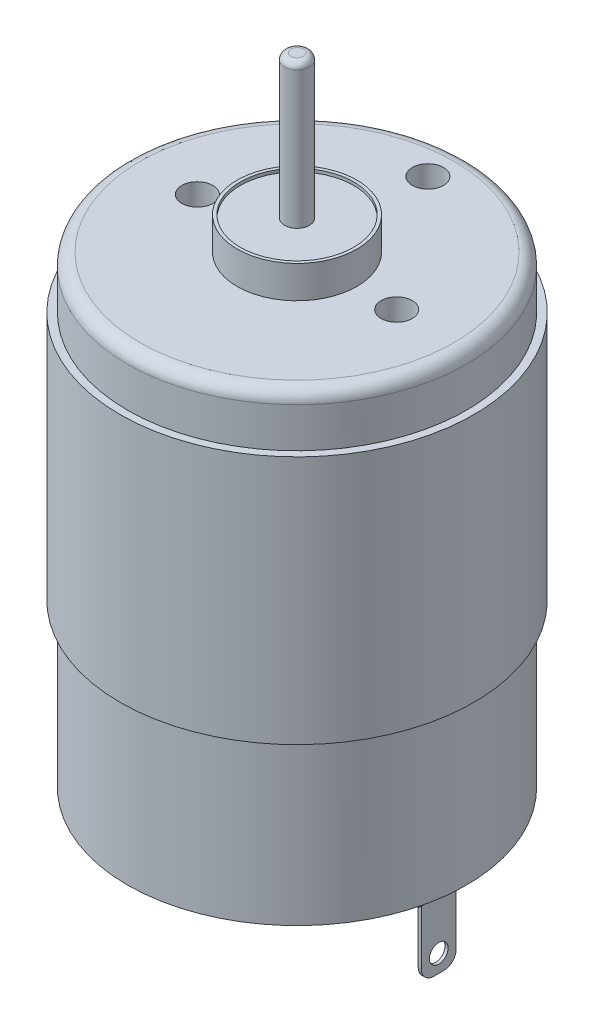
SolidWorks part; units mm, degrees
ref_plane "Plano frontal" through (0, 0, 0) normal (0, 0, 1) x (1, 0, 0)
ref_plane "Plano superior" through (0, 0, 0) normal (0, 1, 0) x (1, 0, 0)
ref_plane "Plano direito" through (0, 0, 0) normal (1, 0, 0) x (0, 0, -1)
sketch "Esboço1" plane through (0, 0, 0) normal (0, 1, 0) x (1, 0, 0)
  circle A0 centre (0, 0) radius 13.6
  dimension "D1" = 27.2
extrude "Ressalto-extrusão1" add sketch "Esboço1" along normal blind 37.2
sketch "Esboço2" plane through (0, 37.2, 0) normal (0, 1, 0) x (1, 0, 0)
  circle A0 centre (0, 0) radius 4.8
  dimension "D1" = 9.6
extrude "Ressalto-extrusão2" add sketch "Esboço2" along normal blind 2.6
sketch "Esboço3" plane through (0, 39.8, 0) normal (0, 1, 0) x (1, 0, 0)
  circle A0 centre (0, 0) radius 4.55
  circle A1 centre (0, 0) radius 4.8 construction
  dimension "D1" = 0.25
extrude "Corte-extrusão1" cut sketch "Esboço3" against normal blind 0.25
sketch "Esboço4" plane through (0, 39.55, 0) normal (0, 1, 0) x (1, 0, 0)
  circle A0 centre (0, 0) radius 1
  dimension "D1" = 2
extrude "Ressalto-extrusão3" add sketch "Esboço4" along normal blind 11.5
fillet "Filete1" radius 0.5 1 edges at (0, 51.05, 1)
sketch "Esboço5" plane through (0, 37.2, 0) normal (0, 1, 0) x (1, 0, 0)
  line L0 (0, 13.6) -> (0, -13.6) construction
  circle A0 centre (-8, 0) radius 1.25
  circle A1 centre (0, 0) radius 13.6 construction
  circle A2 centre (8, 0) radius 1.25
  dimension "D1" = 2.5
  dimension "D2" = 8
extrude "Corte-extrusão2" cut sketch "Esboço5" against normal blind 2
sketch "Esboço6" plane through (0, 37.2, 0) normal (0, 1, 0) x (1, 0, 0)
  circle A0 centre (0, 10.5) radius 1.25
  dimension "D1" = 2.5
  dimension "D2" = 10.5
extrude "Corte-extrusão3" cut sketch "Esboço6" against normal blind 2
sketch "Esboço7" plane through (0, 0, 0) normal (0, -1, 0) x (1, 0, 0)
  circle A0 centre (0, 0) radius 9.5
  circle A1 centre (0, 0) radius 13.35
  circle A2 centre (0, 0) radius 13.6 construction
  dimension "D1" = 19
  dimension "D2" = 0.25
extrude "Corte-extrusão4" cut sketch "Esboço7" against normal blind 0.25
fillet "Filete2" radius 0.2 1 edges at (0, 0, -9.5)
sketch "Esboço8" plane through (0, 0, 0) normal (0, -1, 0) x (1, 0, 0)
  circle A0 centre (0, 0) radius 4.8
  dimension "D1" = 9.6
extrude "Ressalto-extrusão4" add sketch "Esboço8" along normal blind 2.2
sketch "Esboço9" plane through (0, -2.2, 0) normal (0, -1, 0) x (1, 0, 0)
  circle A0 centre (0, 0) radius 4.55
  circle A1 centre (0, 0) radius 4.8 construction
  dimension "D1" = 0.25
extrude "Corte-extrusão5" cut sketch "Esboço9" against normal blind 0.25
sketch "Esboço10" plane through (0, -1.95, 0) normal (0, -1, 0) x (1, 0, 0)
  circle A0 centre (0, 0) radius 1
  dimension "D1" = 2
extrude "Ressalto-extrusão5" add sketch "Esboço10" along normal blind 2.3
fillet "Filete3" radius 0.5 1 edges at (0, -4.25, -1)
fillet "Filete4" radius 1 1 edges at (0, 37.2, 13.6)
sketch "Esboço11" plane through (0, 0.25, 0) normal (0, -1, 0) x (1, 0, 0)
  line L0 (0, 13.35) -> (0, -13.35) construction
  line L1 (-12, -2.25) -> (-10.5, -2.25)
  line L2 (-12, -2.25) -> (-12, 2.25)
  line L3 (-12, 2.25) -> (-10.5, 2.25)
  line L4 (-10.5, -2.25) -> (-10.5, 2.25)
  line L5 (-12, -2.25) -> (-10.5, 2.25) construction
  line L6 (-12, 2.25) -> (-10.5, -2.25) construction
  line L7 (12, 2.25) -> (10.5, -2.25) construction
  line L8 (12, -2.25) -> (10.5, 2.25) construction
  line L9 (10.5, -2.25) -> (10.5, 2.25)
  line L10 (12, 2.25) -> (10.5, 2.25)
  line L11 (12, -2.25) -> (12, 2.25)
  line L12 (12, -2.25) -> (10.5, -2.25)
  circle A0 centre (0, 0) radius 13.35 construction
  circle A1 centre (0, 0) radius 13.35 construction
  point P0 (-11.25, 0)
  point P18 (11.25, 0)
  dimension "D1" = 1.5
  dimension "D2" = 4.5
  dimension "D3" = 12
  dimension "D4" = 0
extrude "Ressalto-extrusão6" add sketch "Esboço11" along normal blind 1.5
sketch "Esboço12" plane through (0, -1.25, 0) normal (0, -1, 0) x (1, 0, 0)
  line L0 (-10.5, 2.25) -> (-12, 2.25) construction
  line L1 (-11.375, -1.4) -> (-11.125, -1.4)
  line L2 (-11.375, -1.4) -> (-11.375, 1.4)
  line L3 (-11.375, 1.4) -> (-11.125, 1.4)
  line L4 (-11.125, -1.4) -> (-11.125, 1.4)
  line L5 (-11.375, -1.4) -> (-11.125, 1.4) construction
  line L6 (-11.375, 1.4) -> (-11.125, -1.4) construction
  line L7 (0, 13.6) -> (0, -13.6) construction
  line L8 (11.375, 1.4) -> (11.125, -1.4) construction
  line L9 (11.375, -1.4) -> (11.125, 1.4) construction
  line L10 (11.125, -1.4) -> (11.125, 1.4)
  line L11 (11.375, 1.4) -> (11.125, 1.4)
  line L12 (11.375, -1.4) -> (11.375, 1.4)
  line L13 (11.375, -1.4) -> (11.125, -1.4)
  circle A0 centre (0, 0) radius 13.6 construction
  point P0 (-11.25, 0)
  point P7 (-11.25, 2.25)
  point P18 (11.25, 0)
  dimension "D1" = 0.25
  dimension "D2" = 0
  dimension "D3" = 2.8
extrude "Ressalto-extrusão7" add sketch "Esboço12" along normal blind 6
sketch "Esboço13" plane through (-11.375, 0, 0) normal (-1, 0, 0) x (0, 0, 1)
  line L1 (1.4, -7.25) -> (-1.4, -7.25) construction
  circle A0 centre (0, -5.85) radius 0.75
  dimension "D1" = 1.5
  dimension "D2" = 1.4
extrude "Corte-extrusão6" cut sketch "Esboço13" against normal through all
fillet "Filete5" radius 1 4 edges at (11.25, -7.25, 1.4) (11.25, -7.25, -1.4) (-11.25, -7.25, 1.4) (-11.25, -7.25, -1.4)
sketch "Esboço14" plane through (0, 0, 0) normal (0, -1, 0) x (1, 0, 0)
  line L0 (0, 0) -> (9.5, 0) construction
  line L1 (0, 0) -> (1.6497, 9.3557) construction
  line L2 (0, 0) -> (-1.6497, -9.3557) construction
  circle A0 centre (0, 0) radius 9.5 construction
  circle A1 centre (1.3024, 7.3861) radius 1
  circle A2 centre (-1.3024, -7.3861) radius 1
  dimension "D2" = 7.5
  dimension "D3" = 2
  dimension "D4" = 2
  dimension "D5" = 7.5
  dimension "D1" = 80
extrude "Corte-extrusão7" cut sketch "Esboço14" against normal blind 2
sketch "Esboço15" plane through (0, 0, 0) normal (0, -1, 0) x (1, 0, 0)
  line L0 (-7.0477, 2.5652) -> (-7.9874, 2.9072) construction
  line L1 (-9.5, 0) -> (9.5, 0) construction
  line L2 (-4.8209, 5.7453) -> (-5.4637, 6.5114) construction
  line L3 (4.8209, -5.7453) -> (5.4637, -6.5114) construction
  line L4 (7.0477, -2.5652) -> (7.9874, -2.9072) construction
  circle A0 centre (0, 0) radius 9.5 construction
  arc A1 (-5.4637, 6.5114) -> (-7.9874, 2.9072) centre (0, 0) ccw
  arc A2 (-4.8209, 5.7453) -> (-7.0477, 2.5652) centre (0, 0) ccw
  arc A3 (4.8209, -5.7453) -> (7.0477, -2.5652) centre (0, 0) ccw
  arc A4 (5.4637, -6.5114) -> (7.9874, -2.9072) centre (0, 0) ccw
  arc A5 (-7.9874, 2.9072) -> (-7.0477, 2.5652) centre (-7.5175, 2.7362) ccw
  arc A6 (-4.8209, 5.7453) -> (-5.4637, 6.5114) centre (-5.1423, 6.1284) ccw
  arc A7 (7.9874, -2.9072) -> (7.0477, -2.5652) centre (7.5175, -2.7362) ccw
  arc A8 (4.8209, -5.7453) -> (5.4637, -6.5114) centre (5.1423, -6.1284) ccw
  dimension "D1" = 17
  dimension "D2" = 15
  dimension "D3" = 20
  dimension "D4" = 50
extrude "Corte-extrusão8" cut sketch "Esboço15" against normal blind 2
sketch "Esboço17" plane through (0, 0, 0) normal (0, -1, 0) x (1, 0, 0)
  line L0 (-1.4, -13.5277) -> (-1.4, -14.1308)
  line L1 (1.4, -13.5277) -> (1.4, -14.1308)
  arc A0 (1.4, -13.5277) -> (-1.4, -13.5277) centre (0, 0) ccw
  arc A1 (1.4, -14.1308) -> (-1.4, -14.1308) centre (0, 0) ccw
  dimension "D1" = 0.6
  dimension "D2" = 27.2
  dimension "D3" = 1.4
  dimension "D4" = 1.4
extrude "Ressalto-extrusão8" add sketch "Esboço17" against normal blind 20 from offset 13
